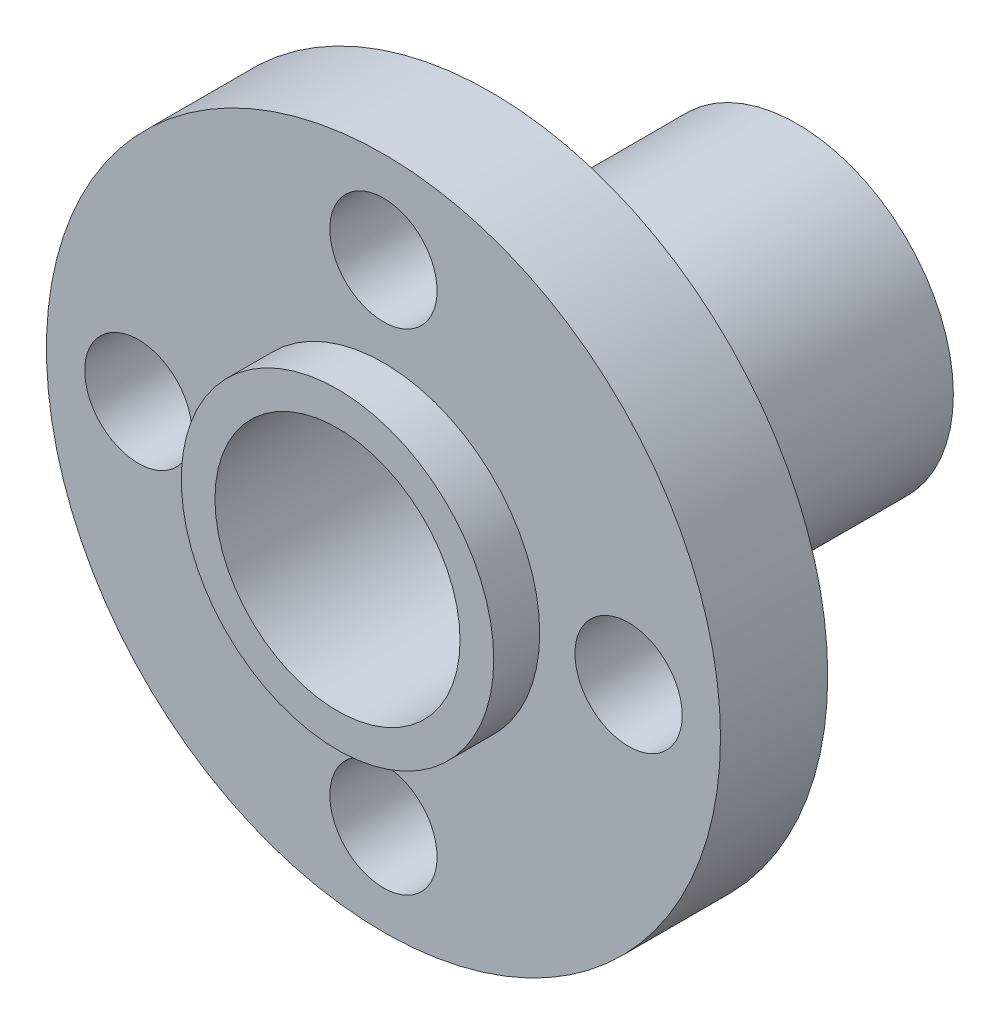
SolidWorks part; units mm, degrees
material "Brass"
ref_plane "Front Plane" through (0, 0, 0) normal (0, 0, 1) x (1, 0, 0)
ref_plane "Top Plane" through (0, 0, 0) normal (0, 1, 0) x (1, 0, 0)
ref_plane "Right Plane" through (0, 0, 0) normal (1, 0, 0) x (0, 0, -1)
sketch "Sketch1" plane through (0, 0, 0) normal (0, 0, 1) x (1, 0, 0)
  circle A0 centre (0, 0) radius 11
  circle A1 centre (0, 0) radius 8
  circle A2 centre (0, 8) radius 1.75
  circle A3 centre (8, 0) radius 1.75
  circle A4 centre (0, -8) radius 1.75
  circle A5 centre (-8, 0) radius 1.75
  circle A6 centre (0, 0) radius 4
  point P15 (0, 0)
  dimension "D1" = 22
  dimension "D2" = 16
  dimension "D3" = 3.5
  dimension "D5" = 8
  dimension "D4" = 4
extrude "Boss-Extrude1" add sketch "Sketch1" along normal blind 3.5 contours A0 A5 A1 A2 A3 A4 | A5 A1 A4 A3 A2 A6
sketch "Sketch2" plane through (0, 0, 0) normal (0, 0, -1) x (-1, 0, 0)
  circle A0 centre (0, 0) radius 5.1
  circle A1 centre (0, 0) radius 4
  dimension "D1" = 10.2
  dimension "D2" = 8
extrude "Boss-Extrude2" add sketch "Sketch2" along normal blind 10
sketch "Sketch3" plane through (0, 0, 3.5) normal (0, 0, 1) x (1, 0, 0)
  circle A0 centre (0, 0) radius 5.1
  circle A1 centre (0, 0) radius 4
  dimension "D1" = 10.2
  dimension "D2" = 8
extrude "Boss-Extrude3" add sketch "Sketch3" along normal blind 1.5
ref_plane "Plane1" through (0, 0, 0) normal (0.7071, -0.7071, 0) x (-0.7071, -0.7071, 0)
